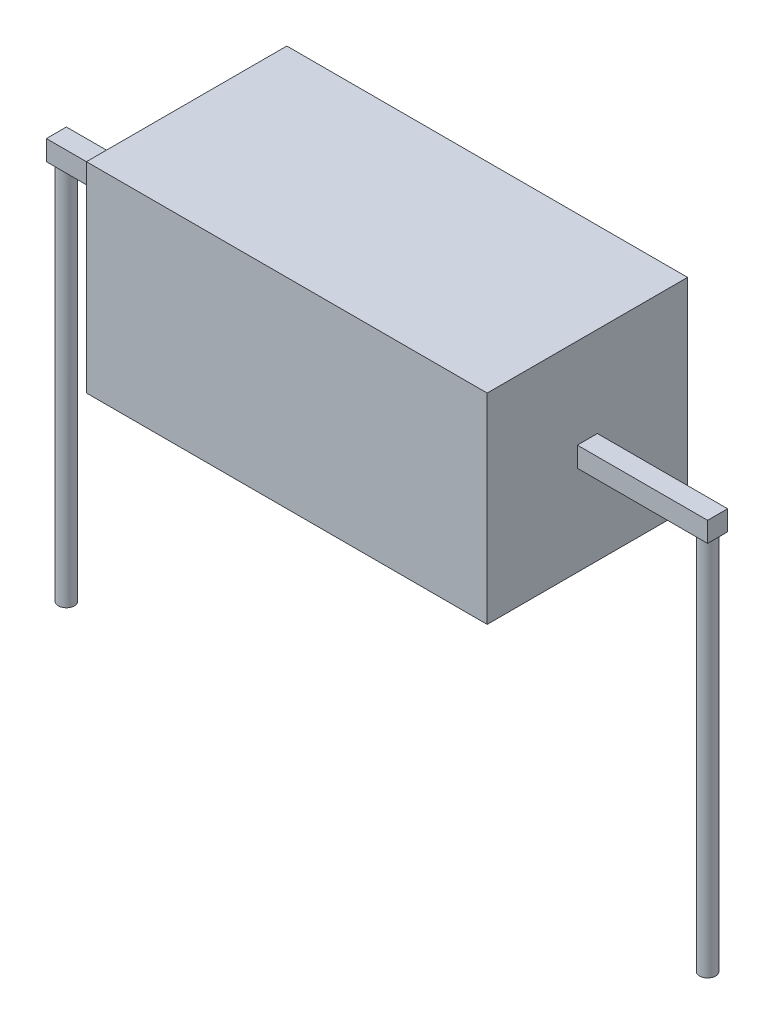
SolidWorks part; units mm, degrees
ref_plane "Спереди" through (0, 0, 0) normal (0, 0, 1) x (1, 0, 0)
ref_plane "Сверху" through (0, 0, 0) normal (0, 1, 0) x (1, 0, 0)
ref_plane "Справа" through (0, 0, 0) normal (1, 0, 0) x (0, 0, -1)
sketch "Эскиз1" plane through (0, 0, 0) normal (0, 0, 1) x (1, 0, 0)
  line L1 (0, 0) -> (20, 0)
  line L2 (0, 0) -> (0, 10)
  line L3 (0, 10) -> (20, 10)
  line L4 (20, 0) -> (20, 10)
  dimension "D1" = 10
  dimension "D2" = 20
extrude "Вытянуть1" add sketch "Эскиз1" along normal blind 10
sketch "Эскиз2" plane through (20, 0, 0) normal (1, 0, 0) x (0, 0, -1)
  line L0 (-10.8705, 5) -> (1.1033, 5) construction
  line L1 (-5, 10.8922) -> (-5, 4.5869) construction
  line L2 (-10, 10) -> (0, 10) construction
  line L3 (-10, 0) -> (0, 0) construction
  line L4 (-10, 0) -> (-10, 10) construction
  line L5 (0, 0) -> (0, 10) construction
  line L7 (-5.5, 4.5) -> (-4.5, 4.5)
  line L8 (-5.5, 4.5) -> (-5.5, 5.5)
  line L9 (-5.5, 5.5) -> (-4.5, 5.5)
  line L10 (-4.5, 4.5) -> (-4.5, 5.5)
  dimension "D1" = 1
extrude "Вытянуть2" add sketch "Эскиз2" along normal blind 6.5 and the other way blind 26.5
sketch "Эскиз3" plane through (0, 4.5, 0) normal (0, -1, 0) x (1, 0, 0)
  line L0 (-6, 5) -> (23.3087, 5) construction
  line L1 (0, 10) -> (20, 10) construction
  line L2 (0, 0) -> (20, 0) construction
  line L3 (10, 11.1302) -> (10, -1.0428) construction
  line L4 (0, 10) -> (0, 0) construction
  line L5 (20, 10) -> (20, 0) construction
  circle A0 centre (-6, 5) radius 0.4
  circle A1 centre (26, 5) radius 0.4
  dimension "D1" = 32
  dimension "D2" = 0.8
extrude "Вытянуть3" add sketch "Эскиз3" along normal blind 19
